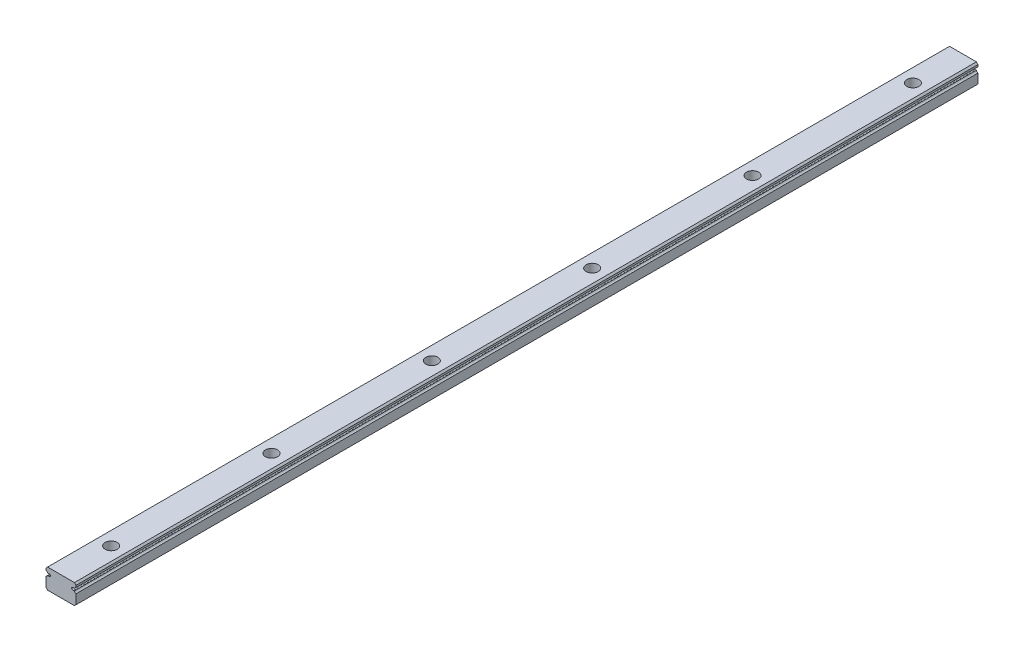
SolidWorks part; units mm, degrees
material "Chrome Stainless Steel"
ref_plane "Front Plane" through (0, 0, 0) normal (0, 0, 1) x (1, 0, 0)
ref_plane "Top Plane" through (0, 0, 0) normal (0, 1, 0) x (1, 0, 0)
ref_plane "Right Plane" through (0, 0, 0) normal (1, 0, 0) x (0, 0, -1)
sketch "Sketch1" plane through (0, 0, 0) normal (0, 0, 1) x (1, 0, 0)
  line L0 (0, 5) -> (0, -5) construction
  line L1 (6.7, -5) -> (-6.7, -5)
  line L2 (-6.7, -5) -> (-7.5, -4.2)
  line L3 (-7.5, -4.2) -> (-7.5, 0.5638)
  line L4 (-7.5, 3.2242) -> (-7.5, 4.2)
  line L5 (-7.5, 4.2) -> (-6.7, 5)
  line L6 (-6.7, 5) -> (6.7, 5)
  line L7 (-6.6245, 1.344) -> (-6.1398, 1.344)
  line L8 (-6.6245, 2.444) -> (-6.1398, 2.444)
  line L9 (6.7, -5) -> (7.5, -4.2)
  line L10 (7.5, -4.2) -> (7.5, 0.5638)
  line L11 (6.6245, 1.344) -> (6.1398, 1.344)
  line L12 (6.6245, 2.444) -> (6.1398, 2.444)
  line L13 (7.5, 3.2242) -> (7.5, 4.2)
  line L14 (7.5, 4.2) -> (6.7, 5)
  circle A0 centre (-5.9, 1.894) radius 0.6 construction
  circle A1 centre (-7.9, 1.894) radius 1.389 construction
  arc A2 (-7.5, 0.5638) -> (-6.6245, 1.344) centre (-7.9, 1.894) ccw
  arc A3 (-6.1398, 1.344) -> (-6.1398, 2.444) centre (-5.9, 1.894) ccw
  arc A4 (-6.6245, 2.444) -> (-7.5, 3.2242) centre (-7.9, 1.894) ccw
  arc A5 (7.5, 0.5638) -> (6.6245, 1.344) centre (7.9, 1.894) cw
  arc A6 (6.1398, 1.344) -> (6.1398, 2.444) centre (5.9, 1.894) cw
  arc A7 (6.6245, 2.444) -> (7.5, 3.2242) centre (7.9, 1.894) cw
  point P4 (0, 0)
  dimension "D1" = 7.5
  dimension "D8" = 2.778
  dimension "D9" = 1.2
  dimension "D10" = 7.9
  dimension "D11" = 6.894
  dimension "D12" = 6.894
  dimension "D5" = 5.9
  dimension "D13" = 0.55
  dimension "D2" = 0.8
  dimension "D3" = 0.8
  dimension "D4" = 10
  dimension "D6" = 0.8
  dimension "D7" = 0.8
  dimension "D14" = 0.55
extrude "Boss-Extrude1" add sketch "Sketch1" against normal blind 450 contours L12 A7 L13 L14 L6 L5 L4 A4 L8 A3 L7 A2 L3 L2 L1 L9 L10 A5 L11 A6
sketch "Sketch2" plane through (0, 5, 0) normal (0, 1, 0) x (1, 0, 0)
  line L0 (-6.7, 0) -> (6.7, 0) construction
  circle A0 centre (0, 25) radius 3
  dimension "D1" = 25
  dimension "D2" = 6
extrude "Cut-Extrude1" cut sketch "Sketch2" against normal blind 4.5
sketch "Sketch3" plane through (0, 0.5, 0) normal (0, 1, 0) x (1, 0, 0)
  circle A0 centre (0, 25) radius 1.75
extrude "Cut-Extrude2" cut sketch "Sketch3" against normal through all
pattern_linear "LPattern1" count 6 spacing 80 along (0, 0, -1) of "Cut-Extrude1", "Cut-Extrude2"
